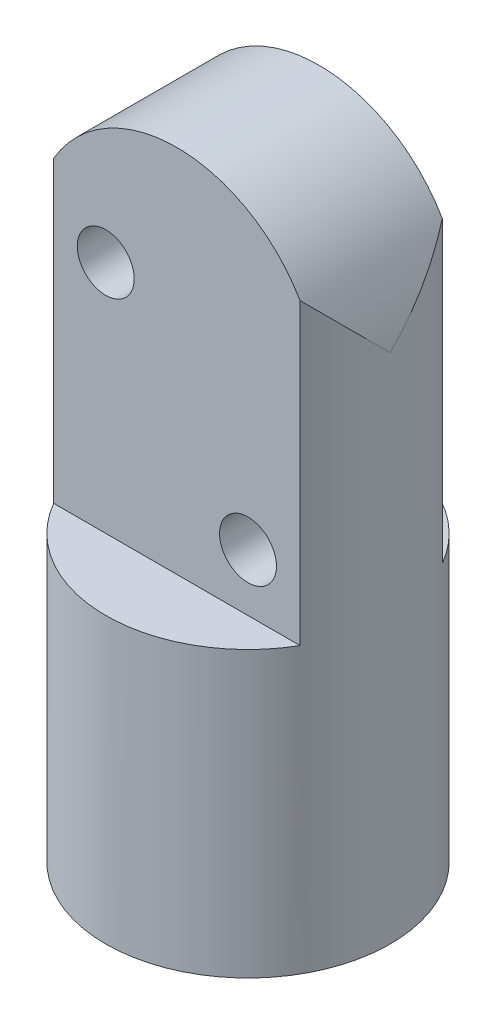
SolidWorks part; units mm, degrees
ref_plane "前视基准面" through (0, 0, 0) normal (0, 0, 1) x (1, 0, 0)
ref_plane "上视基准面" through (0, 0, 0) normal (0, 1, 0) x (1, 0, 0)
ref_plane "右视基准面" through (0, 0, 0) normal (1, 0, 0) x (0, 0, -1)
other "Configuration Table"
sketch "草图1" plane through (0, 0, 0) normal (0, 1, 0) x (1, 0, 0)
  circle A0 centre (0, 0) radius 25
  circle A1 centre (0, 0) radius 10
  dimension "D1" = 20
  dimension "D2" = 50
extrude "凸台-拉伸1" add sketch "草图1" along normal blind 50
sketch "草图2" plane through (0, 0, 0) normal (0, 0, 1) x (1, 0, 0)
  line L0 (-25, 50) -> (25, 50)
  line L1 (25, 50) -> (25, 90)
  line L2 (-25, 50) -> (-25, 90)
  arc A0 (-25, 90) -> (25, 90) centre (0, 90) cw
  dimension "D1" = 40
extrude "凸台-拉伸2" add sketch "草图2" along normal mid plane 25
sketch "草图4" plane through (0, 50, 0) normal (0, -1, 0) x (1, 0, 0)
  line L0 (25, -12.5) -> (25, 0) construction
  line L1 (21.6506, -12.5) -> (25, -12.5) construction
  line L2 (-25, -12.5) -> (-21.6506, -12.5) construction
  line L3 (-25, 0) -> (-25, -12.5) construction
  line L4 (-25, 12.5) -> (-25, 0) construction
  line L5 (-21.6506, 12.5) -> (-25, 12.5) construction
  line L6 (25, 12.5) -> (21.6506, 12.5) construction
  line L7 (25, 0) -> (25, 12.5) construction
  line L8 (25, -12.5) -> (25, 0)
  line L9 (21.6506, -12.5) -> (25, -12.5)
  line L10 (-25, -12.5) -> (-21.6506, -12.5)
  line L11 (-25, 0) -> (-25, -12.5)
  line L12 (-25, 12.5) -> (-25, 0)
  line L13 (-21.6506, 12.5) -> (-25, 12.5)
  line L14 (25, 12.5) -> (21.6506, 12.5)
  line L15 (25, 0) -> (25, 12.5)
  arc A0 (21.6506, -12.5) -> (25, 0) centre (0, 0) ccw construction
  arc A1 (-25, 0) -> (-21.6506, -12.5) centre (0, 0) ccw construction
  arc A2 (-21.6506, 12.5) -> (-25, 0) centre (0, 0) ccw construction
  arc A3 (25, 0) -> (21.6506, 12.5) centre (0, 0) ccw construction
  arc A4 (21.6506, -12.5) -> (25, 0) centre (0, 0) ccw
  arc A5 (-25, 0) -> (-21.6506, -12.5) centre (0, 0) ccw
  arc A6 (-21.6506, 12.5) -> (-25, 0) centre (0, 0) ccw
  arc A7 (25, 0) -> (21.6506, 12.5) centre (0, 0) ccw
extrude "切除-拉伸1" cut sketch "草图4" against normal through all contours A4 L9 L8 | A6 L13 L12 | A5 L11 L10
sketch "草图5" plane through (0, 0, 12.5) normal (0, 0, 1) x (1, 0, 0)
  line L0 (21.6506, 50) -> (-21.6506, 50) construction
  circle A2 centre (-12.5, 91.225) radius 5
  circle A3 centre (12.5, 60) radius 5
  dimension "D1" = 10
  dimension "D2" = 10
  dimension "D3" = 10
  dimension "D4" = 40
  dimension "D5" = 25
  dimension "D6" = 12.5
extrude "切除-拉伸2" cut sketch "草图5" against normal through all
